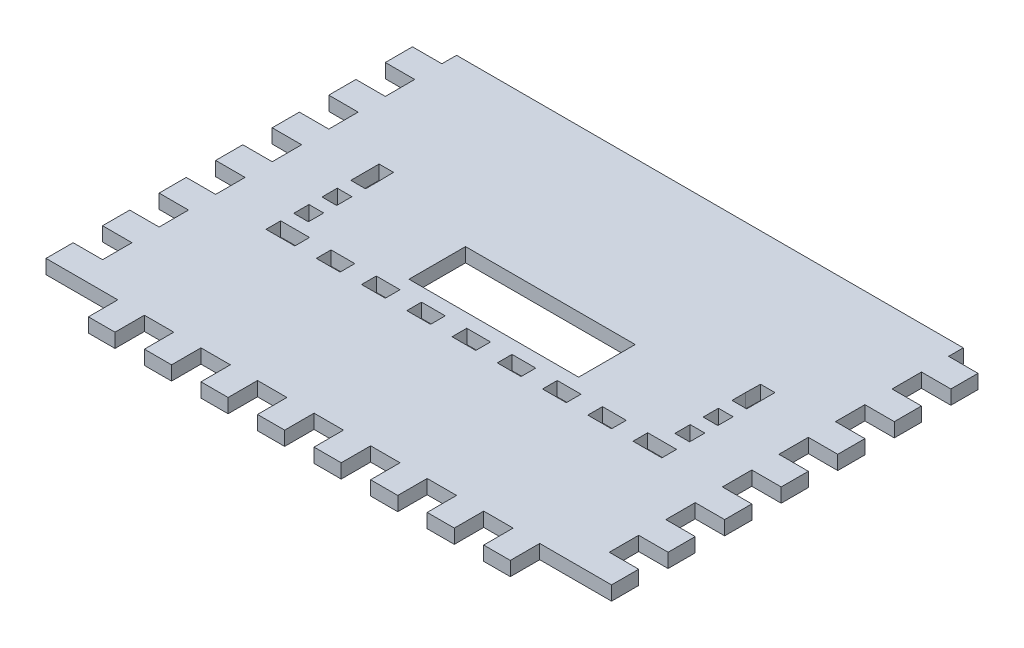
SolidWorks part; units mm, degrees
ref_plane "Front Plane" through (0, 0, 0) normal (0, 0, 1) x (1, 0, 0)
ref_plane "Top Plane" through (0, 0, 0) normal (0, 1, 0) x (1, 0, 0)
ref_plane "Right Plane" through (0, 0, 0) normal (1, 0, 0) x (0, 0, -1)
sketch "Sketch1" plane through (0, 0, 0) normal (0, 1, 0) x (1, 0, 0)
  line L1 (-63.5, -53.975) -> (63.5, -53.975)
  line L2 (-63.5, -53.975) -> (-63.5, 53.975)
  line L3 (-63.5, 53.975) -> (63.5, 53.975)
  line L4 (63.5, -53.975) -> (63.5, 53.975)
  line L5 (-63.5, -53.975) -> (63.5, 53.975) construction
  line L6 (-63.5, 53.975) -> (63.5, -53.975) construction
  point P0 (0, 0)
  dimension "D1" = 127
  dimension "D2" = 107.95
extrude "Boss-Extrude1" add sketch "Sketch1" along normal blind 3.175
sketch "Sketch2" plane through (0, 0, 0) normal (0, -1, 0) x (1, 0, 0)
  line L5 (63.5, 53.975) -> (63.5, -53.975) construction
  line L34 (0, 0) -> (0, -14.8721) construction
  line L39 (63.5, 25.527) -> (56.896, 25.527)
  line L41 (63.5, 38.227) -> (63.5, 31.623)
  line L42 (63.5, 31.623) -> (56.896, 31.623)
  line L44 (63.5, 25.527) -> (63.5, 18.923)
  line L45 (63.5, 18.923) -> (56.896, 18.923)
  line L46 (56.896, 25.527) -> (56.896, 18.923)
  line L47 (63.5, 12.827) -> (56.896, 12.827)
  line L48 (63.5, 12.827) -> (63.5, 6.223)
  line L49 (63.5, 6.223) -> (56.896, 6.223)
  line L50 (56.896, 12.827) -> (56.896, 6.223)
  line L51 (63.5, 0.127) -> (56.896, 0.127)
  line L52 (63.5, 0.127) -> (63.5, -6.477)
  line L53 (63.5, -6.477) -> (56.896, -6.477)
  line L54 (56.896, 0.127) -> (56.896, -6.477)
  line L55 (63.5, -12.573) -> (56.896, -12.573)
  line L56 (63.5, -12.573) -> (63.5, -19.177)
  line L57 (63.5, -19.177) -> (56.896, -19.177)
  line L58 (56.896, -12.573) -> (56.896, -19.177)
  line L59 (63.5, -25.273) -> (56.896, -25.273)
  line L60 (63.5, -25.273) -> (63.5, -31.877)
  line L61 (63.5, -31.877) -> (56.896, -31.877)
  line L62 (56.896, -25.273) -> (56.896, -31.877)
  line L63 (63.5, -37.973) -> (56.896, -37.973)
  line L64 (63.5, -37.973) -> (63.5, -44.577)
  line L65 (63.5, -44.577) -> (56.896, -44.577)
  line L66 (56.896, -37.973) -> (56.896, -44.577)
  line L67 (63.5, -50.673) -> (56.896, -50.673)
  line L68 (63.5, -50.673) -> (63.5, -57.277)
  line L69 (63.5, -57.277) -> (56.896, -57.277)
  line L70 (56.896, -50.673) -> (56.896, -57.277)
  line L71 (-56.896, -50.673) -> (-56.896, -57.277)
  line L72 (-63.5, -57.277) -> (-56.896, -57.277)
  line L73 (-63.5, -50.673) -> (-63.5, -57.277)
  line L74 (-63.5, -50.673) -> (-56.896, -50.673)
  line L75 (-56.896, -37.973) -> (-56.896, -44.577)
  line L76 (-63.5, -44.577) -> (-56.896, -44.577)
  line L77 (-63.5, -37.973) -> (-63.5, -44.577)
  line L78 (-63.5, -37.973) -> (-56.896, -37.973)
  line L79 (-56.896, -25.273) -> (-56.896, -31.877)
  line L80 (-63.5, -31.877) -> (-56.896, -31.877)
  line L81 (-63.5, -25.273) -> (-63.5, -31.877)
  line L82 (-63.5, -25.273) -> (-56.896, -25.273)
  line L83 (-56.896, -12.573) -> (-56.896, -19.177)
  line L84 (-63.5, -19.177) -> (-56.896, -19.177)
  line L85 (-63.5, -12.573) -> (-63.5, -19.177)
  line L86 (-63.5, -12.573) -> (-56.896, -12.573)
  line L87 (-56.896, 0.127) -> (-56.896, -6.477)
  line L88 (-63.5, -6.477) -> (-56.896, -6.477)
  line L89 (-63.5, 0.127) -> (-63.5, -6.477)
  line L90 (-63.5, 0.127) -> (-56.896, 0.127)
  line L91 (-56.896, 12.827) -> (-56.896, 6.223)
  line L92 (-63.5, 6.223) -> (-56.896, 6.223)
  line L93 (-63.5, 12.827) -> (-63.5, 6.223)
  line L94 (-63.5, 12.827) -> (-56.896, 12.827)
  line L95 (-56.896, 25.527) -> (-56.896, 18.923)
  line L96 (-63.5, 18.923) -> (-56.896, 18.923)
  line L97 (-63.5, 25.527) -> (-63.5, 18.923)
  line L99 (-63.5, 31.623) -> (-56.896, 31.623)
  line L100 (-63.5, 38.227) -> (-63.5, 31.623)
  line L102 (-63.5, 25.527) -> (-56.896, 25.527)
  line L103 (56.896, 31.623) -> (47.371, 31.623)
  line L104 (47.371, 31.623) -> (47.371, 38.227)
  line L105 (47.371, 38.227) -> (41.402, 38.227)
  line L106 (41.402, 38.227) -> (41.402, 31.623)
  line L107 (41.402, 31.623) -> (34.798, 31.623)
  line L108 (34.798, 31.623) -> (34.798, 38.227)
  line L109 (34.798, 38.227) -> (28.702, 38.227)
  line L110 (28.702, 38.227) -> (28.702, 31.623)
  line L111 (28.702, 31.623) -> (22.098, 31.623)
  line L112 (22.098, 31.623) -> (22.098, 38.227)
  line L113 (22.098, 38.227) -> (16.002, 38.227)
  line L114 (16.002, 38.227) -> (16.002, 31.623)
  line L115 (16.002, 31.623) -> (9.398, 31.623)
  line L116 (9.398, 31.623) -> (9.398, 38.227)
  line L117 (9.398, 38.227) -> (3.302, 38.227)
  line L118 (3.302, 38.227) -> (3.302, 31.623)
  line L119 (3.302, 31.623) -> (-3.302, 31.623)
  line L120 (-3.302, 31.623) -> (-3.302, 38.227)
  line L121 (-3.302, 38.227) -> (-9.398, 38.227)
  line L122 (-9.398, 38.227) -> (-9.398, 31.623)
  line L123 (-9.398, 31.623) -> (-16.002, 31.623)
  line L124 (-16.002, 31.623) -> (-16.002, 38.227)
  line L125 (-16.002, 38.227) -> (-22.098, 38.227)
  line L126 (-22.098, 38.227) -> (-22.098, 31.623)
  line L127 (-22.098, 31.623) -> (-28.702, 31.623)
  line L128 (-28.702, 31.623) -> (-28.702, 38.227)
  line L129 (-28.702, 38.227) -> (-34.798, 38.227)
  line L130 (-34.798, 38.227) -> (-34.798, 31.623)
  line L131 (-34.798, 31.623) -> (-41.402, 31.623)
  line L132 (-41.402, 31.623) -> (-41.402, 38.227)
  line L133 (-41.402, 38.227) -> (-47.371, 38.227)
  line L134 (-47.371, 38.227) -> (-47.371, 31.623)
  line L135 (-47.371, 31.623) -> (-56.896, 31.623)
  line L136 (63.5, 38.227) -> (63.5, 53.975)
  line L138 (63.5, 53.975) -> (-63.5, 53.975)
  line L139 (-63.5, 53.975) -> (-63.5, 38.227)
  dimension "D8" = 6.604
extrude "Cut-Extrude1" cut sketch "Sketch2" against normal through all
sketch "Sketch3" plane through (0, 0, 0) normal (0, 1, 0) x (1, 0, 0)
  line L52 (44.45, 24.13) -> (41.2115, 24.13)
  line L81 (41.148, 20.828) -> (41.2115, 24.13)
  line L100 (0.3587, 11.43) -> (0.3587, 4.953) construction
  line L101 (44.45, -1.27) -> (37.973, -1.27)
  line L102 (44.45, -1.27) -> (44.45, 2.032)
  line L103 (44.45, 2.032) -> (37.973, 2.032)
  line L104 (37.973, -1.27) -> (37.973, 2.032)
  line L105 (44.45, 17.78) -> (41.148, 17.78)
  line L106 (44.45, 4.953) -> (41.148, 4.953)
  line L107 (44.45, 4.953) -> (44.45, 8.382)
  line L108 (44.45, 8.382) -> (41.148, 8.382)
  line L109 (41.148, 4.953) -> (41.148, 8.382)
  line L110 (41.148, 17.78) -> (41.148, 20.828)
  line L114 (44.45, 24.13) -> (44.45, 17.78)
  line L115 (44.45, 11.303) -> (41.148, 11.303)
  line L116 (44.45, 11.303) -> (44.45, 14.732)
  line L117 (44.45, 14.732) -> (41.148, 14.732)
  line L118 (41.148, 11.303) -> (41.148, 14.732)
  line L147 (33.147, -1.27) -> (33.147, 2.032)
  line L148 (27.813, 2.032) -> (33.147, 2.032)
  line L149 (27.813, -1.27) -> (27.813, 2.032)
  line L150 (27.813, -1.27) -> (33.147, -1.27)
  line L151 (22.987, -1.27) -> (22.987, 2.032)
  line L152 (17.653, 2.032) -> (22.987, 2.032)
  line L153 (17.653, -1.27) -> (17.653, 2.032)
  line L154 (17.653, -1.27) -> (22.987, -1.27)
  line L155 (12.827, -1.27) -> (12.827, 2.032)
  line L156 (7.493, 2.032) -> (12.827, 2.032)
  line L157 (7.493, -1.27) -> (7.493, 2.032)
  line L158 (7.493, -1.27) -> (12.827, -1.27)
  line L159 (2.667, -1.27) -> (2.667, 2.032)
  line L160 (-2.667, 2.032) -> (2.667, 2.032)
  line L161 (-2.667, -1.27) -> (-2.667, 2.032)
  line L162 (-2.667, -1.27) -> (2.667, -1.27)
  line L163 (-7.493, -1.27) -> (-7.493, 2.032)
  line L164 (-12.827, 2.032) -> (-7.493, 2.032)
  line L165 (-12.827, -1.27) -> (-12.827, 2.032)
  line L166 (-12.827, -1.27) -> (-7.493, -1.27)
  line L167 (-17.653, -1.27) -> (-17.653, 2.032)
  line L168 (-22.987, 2.032) -> (-17.653, 2.032)
  line L169 (-22.987, -1.27) -> (-22.987, 2.032)
  line L170 (-22.987, -1.27) -> (-17.653, -1.27)
  line L171 (-41.148, 11.303) -> (-41.148, 14.732)
  line L172 (-44.45, 14.732) -> (-41.148, 14.732)
  line L173 (-44.45, 11.303) -> (-44.45, 14.732)
  line L174 (-44.45, 11.303) -> (-41.148, 11.303)
  line L175 (-44.45, 24.13) -> (-44.45, 17.78)
  line L179 (-41.148, 17.78) -> (-41.148, 20.828)
  line L180 (-41.148, 4.953) -> (-41.148, 8.382)
  line L181 (-44.45, 8.382) -> (-41.148, 8.382)
  line L182 (-44.45, 4.953) -> (-44.45, 8.382)
  line L183 (-44.45, 4.953) -> (-41.148, 4.953)
  line L184 (-44.45, 17.78) -> (-41.148, 17.78)
  line L185 (-27.813, -1.27) -> (-27.813, 2.032)
  line L186 (-33.147, 2.032) -> (-27.813, 2.032)
  line L187 (-33.147, -1.27) -> (-33.147, 2.032)
  line L188 (-33.147, -1.27) -> (-27.813, -1.27)
  line L189 (-37.973, -1.27) -> (-37.973, 2.032)
  line L190 (-44.45, 2.032) -> (-37.973, 2.032)
  line L191 (-44.45, -1.27) -> (-44.45, 2.032)
  line L192 (-44.45, -1.27) -> (-37.973, -1.27)
  line L193 (-41.148, 20.828) -> (-41.2115, 24.13)
  line L194 (-41.2115, 24.13) -> (-44.45, 24.13)
  line L196 (19.4087, 5.08) -> (-18.6913, 5.08)
  line L197 (19.4087, 5.08) -> (19.4087, 17.78)
  line L198 (19.4087, 17.78) -> (-18.6913, 17.78)
  line L199 (-18.6913, 5.08) -> (-18.6913, 17.78)
  line L200 (19.4087, 5.08) -> (-18.6913, 17.78) construction
  line L201 (19.4087, 17.78) -> (-18.6913, 5.08) construction
  dimension "D1" = 12.7
  dimension "D2" = 38.1
extrude "Cut-Extrude2" cut sketch "Sketch3" along normal through all
